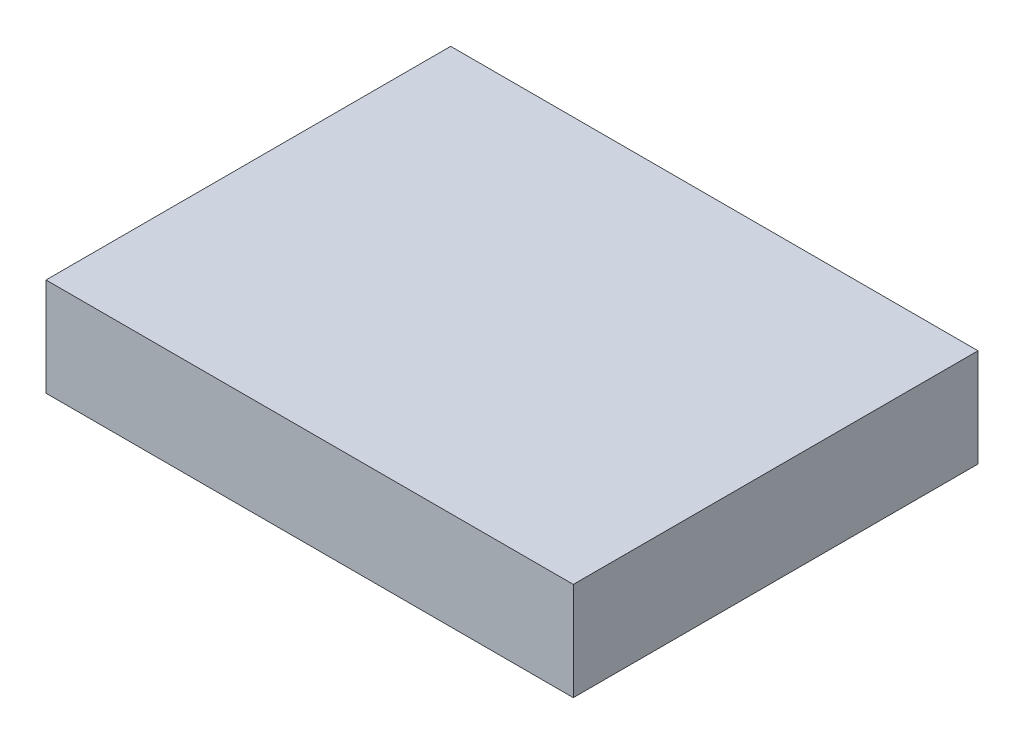
SolidWorks part; units mm, degrees
ref_plane "Front Plane" through (0, 0, 0) normal (0, 0, 1) x (1, 0, 0)
ref_plane "Top Plane" through (0, 0, 0) normal (0, 1, 0) x (1, 0, 0)
ref_plane "Right Plane" through (0, 0, 0) normal (1, 0, 0) x (0, 0, -1)
sketch "Sketch1" plane through (0, 0, 0) normal (0, 1, 0) x (1, 0, 0)
  line L1 (-43, -33) -> (43, -33)
  line L2 (-43, -33) -> (-43, 33)
  line L3 (-43, 33) -> (43, 33)
  line L4 (43, -33) -> (43, 33)
  line L5 (-43, -33) -> (43, 33) construction
  line L6 (-43, 33) -> (43, -33) construction
  point P0 (0, 0)
extrude "Boss-Extrude1" add sketch "Sketch1" along normal blind 16
sketch "Sketch2" plane through (0, 0, 0) normal (0, -1, 0) x (1, 0, 0)
  line L1 (-40.6, -30.6) -> (40.6, -30.6)
  line L2 (-40.6, -30.6) -> (-40.6, 30.6)
  line L3 (-40.6, 30.6) -> (40.6, 30.6)
  line L4 (40.6, -30.6) -> (40.6, 30.6)
  line L5 (-40.6, -30.6) -> (40.6, 30.6) construction
  line L6 (-40.6, 30.6) -> (40.6, -30.6) construction
  point P0 (0, 0)
extrude "Cut-Extrude1" cut sketch "Sketch2" against normal blind 13.6
sketch "Sketch3" plane through (0, 13.6, 0) normal (0, -1, 0) x (1, 0, 0)
  line L1 (-5.5, -7) -> (19.5, -7)
  line L2 (-5.5, -7) -> (-5.5, 7)
  line L3 (-5.5, 7) -> (19.5, 7)
  line L4 (19.5, -7) -> (19.5, 7)
  line L5 (-5.5, -7) -> (19.5, 7) construction
  line L6 (-5.5, 7) -> (19.5, -7) construction
  circle A0 centre (0, -12.5) radius 2.75
  circle A1 centre (10, -12.5) radius 2.75
  circle A2 centre (25, -9) radius 1.25
  circle A3 centre (28.2, -9) radius 0.9
  circle A4 centre (27.3, -6.2287) radius 0.9
  circle A5 centre (23.4, -6.2287) radius 1.6
  circle A6 centre (21.8, -9) radius 1.6
  circle A7 centre (23.4, -12.5) radius 1.6
  circle A8 centre (27.3, -12.5) radius 0.9
  circle A9 centre (25, 12) radius 5.5
  circle A10 centre (-7, -21) radius 1.5
  circle A11 centre (-1, -21) radius 1
  circle A12 centre (5, -21) radius 1.1
  circle A13 centre (11, -21) radius 1.1
  point P0 (7, 0)
